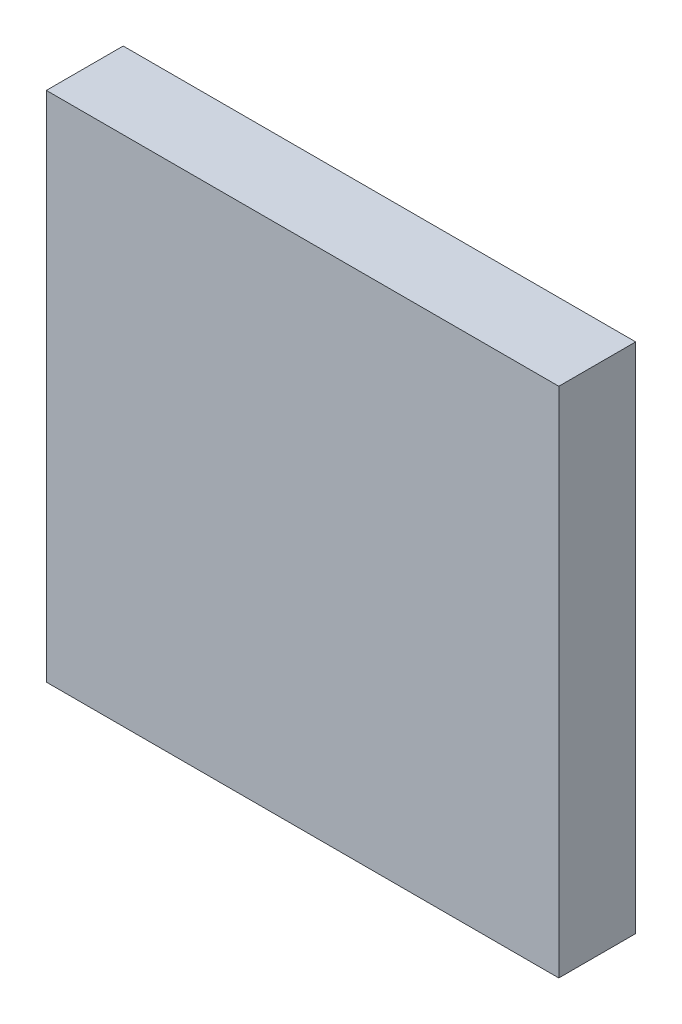
SolidWorks part; units mm, degrees
ref_plane "Front Plane" through (0, 0, 0) normal (0, 0, 1) x (1, 0, 0)
ref_plane "Top Plane" through (0, 0, 0) normal (0, 1, 0) x (1, 0, 0)
ref_plane "Right Plane" through (0, 0, 0) normal (1, 0, 0) x (0, 0, -1)
sketch "Sketch1" plane through (0, 0, 0) normal (0, 0, 1) x (1, 0, 0)
  line L0 (-3.5, -3.5) -> (-3.5, 3.5)
  line L1 (-3.5, 3.5) -> (3.5, 3.5)
  line L2 (3.5, 3.5) -> (3.5, -3.5)
  line L3 (3.5, -3.5) -> (-3.5, -3.5)
extrude "Component_Outline" add sketch "Sketch1" along normal blind 1.05 separate body
sketch3d "3DSketch1"
  line L0 (0, 0, 0) -> (1, 0, 0)
  line L1 (0, 0, 0) -> (0, 1, 0)
  line L2 (0, 0, 0) -> (0, 0, 1)
  point P0 (0, 0, 0)
